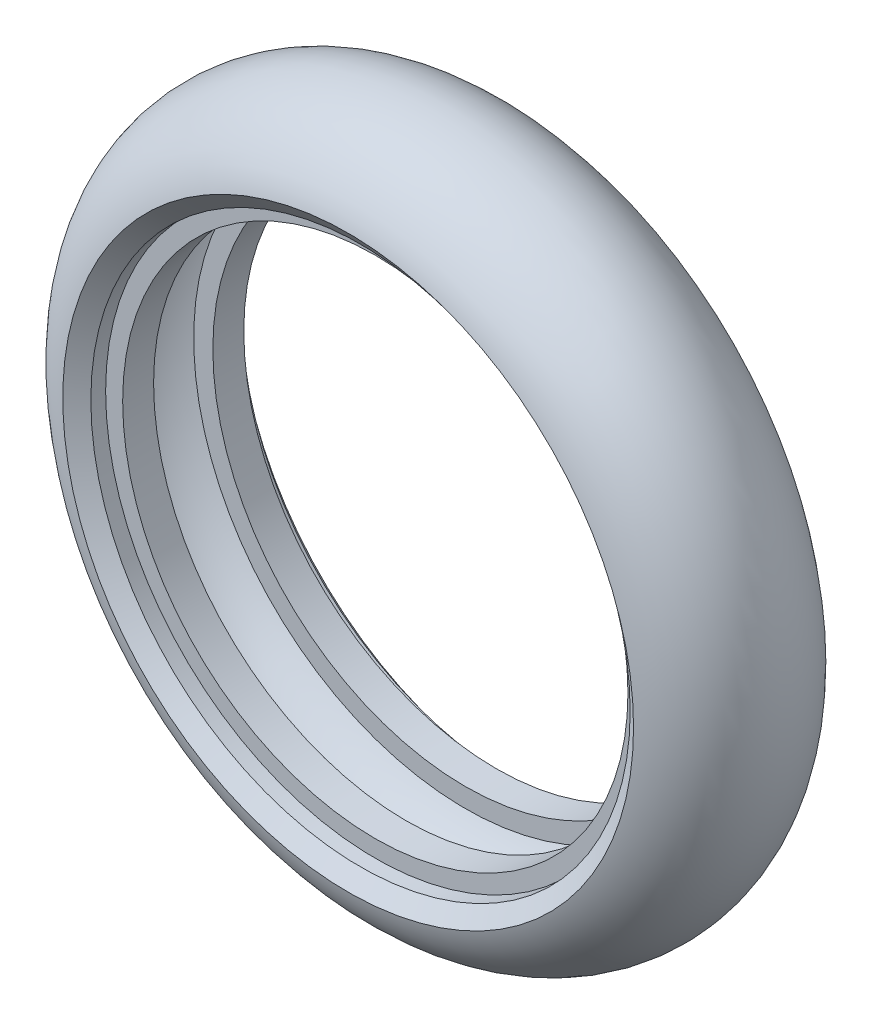
SolidWorks part; units mm, degrees
ref_plane "Piano frontale" through (0, 0, 0) normal (0, 0, 1) x (1, 0, 0)
ref_plane "Piano superiore" through (0, 0, 0) normal (0, 1, 0) x (1, 0, 0)
ref_plane "Piano destro" through (0, 0, 0) normal (1, 0, 0) x (0, 0, -1)
sketch "Schizzo1" plane through (0, 0, 0) normal (1, 0, 0) x (0, 0, -1)
  line L0 (-13.75, -3.753) -> (-11.815, -1.288)
  line L1 (0, -14.253) -> (0, 6.5173) construction
  line L2 (-11.815, -1.288) -> (-9.495, -1.288)
  line L3 (-9.495, -1.288) -> (-9.495, 1.382)
  line L4 (-9.495, 1.382) -> (-4.645, 1.382)
  line L5 (-4.645, 1.382) -> (-4.645, -1.618)
  line L6 (-11.5257, -4.1585) -> (-10.2418, -2.5229)
  line L8 (-4.645, -1.618) -> (-10.2418, -2.5229)
  line L9 (4.645, -1.618) -> (10.2418, -2.5229)
  line L10 (11.5257, -4.1585) -> (10.2418, -2.5229)
  line L11 (4.645, 1.382) -> (4.645, -1.618)
  line L12 (9.495, 1.382) -> (4.645, 1.382)
  line L13 (9.495, -1.288) -> (9.495, 1.382)
  line L14 (11.815, -1.288) -> (9.495, -1.288)
  line L15 (13.75, -3.753) -> (11.815, -1.288)
  line L16 (-83.137, 40.997) -> (60.7707, 40.997) construction
  arc A0 (-13.75, -3.753) -> (0, -14.253) centre (0, 0) ccw
  arc A1 (-11.5257, -4.1585) -> (0, -12.253) centre (0, 0) ccw
  arc A2 (11.5257, -4.1585) -> (0, -12.253) centre (0, 0) cw
  arc A3 (13.75, -3.753) -> (0, -14.253) centre (0, 0) cw
  dimension "D1" = 2
  dimension "D2" = 27.5
  dimension "D3" = 2.32
  dimension "D4" = 18.99
  dimension "D5" = 4.85
  dimension "D6" = 79.23
  dimension "D7" = 2.67
  dimension "D8" = 3
  dimension "D9" = 110.5
  dimension "D10" = 10.5
revolve "Rivoluzione1" add sketch "Schizzo1" angle 360 about L16
